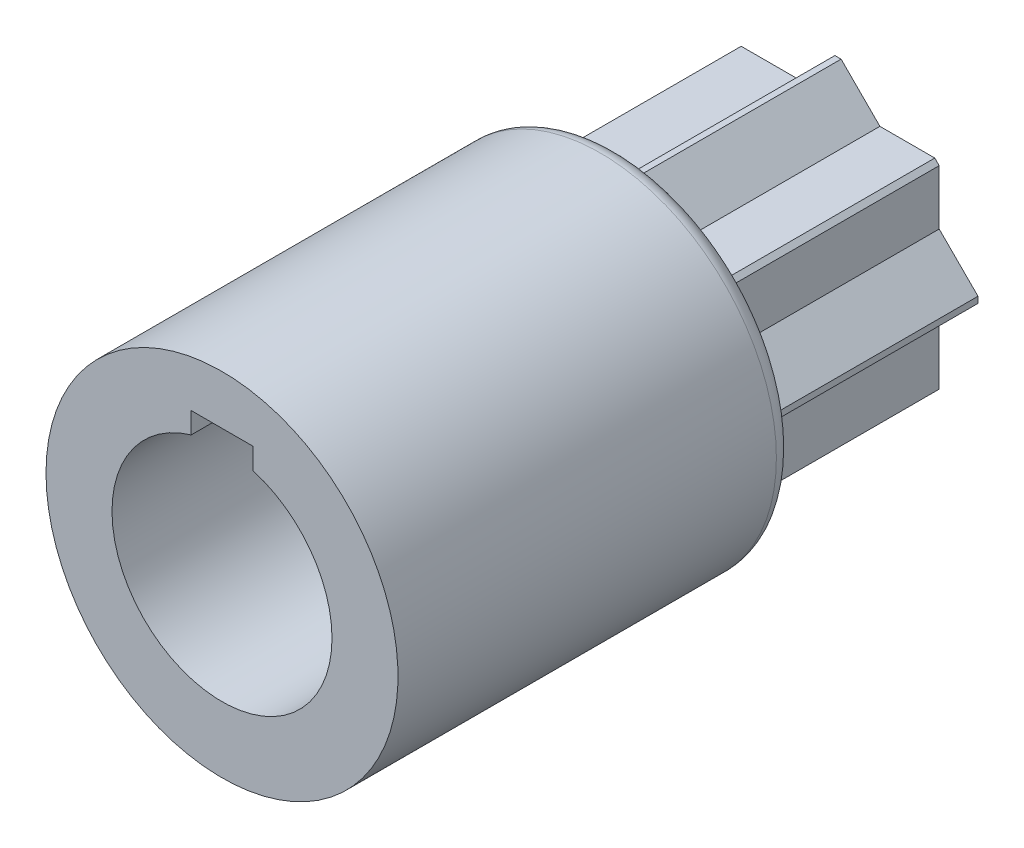
SolidWorks part; units mm, degrees
material "Mo40"
ref_plane "Front Plane" through (0, 0, 0) normal (0, 0, 1) x (1, 0, 0)
ref_plane "Top Plane" through (0, 0, 0) normal (0, 1, 0) x (1, 0, 0)
ref_plane "Right Plane" through (0, 0, 0) normal (1, 0, 0) x (0, 0, -1)
sketch "Sketch1" plane through (0, 0, 0) normal (0, 0, 1) x (1, 0, 0)
  line L0 (0.7071, -31.8198) -> (9.5269, -23)
  line L1 (-22, -23) -> (-9.5269, -23)
  line L2 (-23, -22) -> (-23, -9.5269)
  line L3 (-22, 23) -> (-9.5269, 23)
  line L4 (23, -22) -> (23, -9.5269)
  line L5 (-23, -23) -> (23, 23) construction
  line L6 (-23, 23) -> (23, -23) construction
  line L7 (-0.7071, -31.8198) -> (-9.5269, -23)
  line L8 (31.8198, 0.7071) -> (23, 9.5269)
  line L9 (-31.8198, 0.7071) -> (-23, 9.5269)
  line L10 (0, -32.5269) -> (0, 32.5269) construction
  line L11 (32.5269, 0) -> (-32.5269, 0) construction
  line L12 (-9.5269, 23) -> (-0.7071, 31.8198)
  line L13 (-23, 9.5269) -> (-23, 22)
  line L14 (-23, -9.5269) -> (-31.8198, -0.7071)
  line L15 (9.5269, -23) -> (22, -23)
  line L16 (23, -9.5269) -> (31.8198, -0.7071)
  line L17 (23, 9.5269) -> (23, 22)
  line L18 (9.5269, 23) -> (0.7071, 31.8198)
  line L19 (9.5269, 23) -> (22, 23)
  line L20 (0.7071, 31.8198) -> (-0.7071, 31.8198)
  line L21 (-23, 22) -> (-22, 23)
  line L22 (-31.8198, -0.7071) -> (-31.8198, 0.7071)
  line L23 (-23, -22) -> (-22, -23)
  line L24 (0.7071, -31.8198) -> (-0.7071, -31.8198)
  line L25 (22, -23) -> (23, -22)
  line L26 (31.8198, -0.7071) -> (31.8198, 0.7071)
  line L27 (22, 23) -> (23, 22)
  point P0 (0, 0)
  point P7 (0, 0)
  dimension "D1" = 46
  dimension "D2" = 46
  dimension "D3" = 46
  dimension "D4" = 46
extrude "Boss-Extrude1" add sketch "Sketch1" along normal blind 50
sketch "Sketch2" plane through (0, 0, 50) normal (0, 0, 1) x (1, 0, 0)
  circle A0 centre (0, 0) radius 40
  dimension "D1" = 80
extrude "Boss-Extrude2" add sketch "Sketch2" along normal blind 90
ref_plane "Plane1" [suppressed] through (0, 25, 0) normal (0, 1, 0) x (1, 0, 0)
sketch "Sketch3" plane through (0, 0, 140) normal (0, 0, 1) x (1, 0, 0)
  circle A0 centre (0, 0) radius 25
  dimension "D1" = 50
extrude "Cut-Extrude1" cut sketch "Sketch3" against normal blind 67
sketch "Sketch4" plane through (0, 0, 140) normal (0, 0, 1) x (1, 0, 0)
  line L1 (-7, 0) -> (7, 0)
  line L2 (-7, 0) -> (-7, 28.8)
  line L3 (-7, 28.8) -> (7, 28.8)
  line L4 (7, 0) -> (7, 28.8)
  line L5 (-7, 0) -> (7, 28.8) construction
  line L6 (-7, 28.8) -> (7, 0) construction
  point P0 (0, 14.4)
  dimension "D1" = 28.8
  dimension "D2" = 14
extrude "Cut-Extrude2" cut sketch "Sketch4" against normal blind 65
fillet "Fillet1" radius 4 1 edges at (40, 0, 50)
chamfer "Chamfer1" distance 0.5 angle 45 1 edges at (25, 0, 73)
